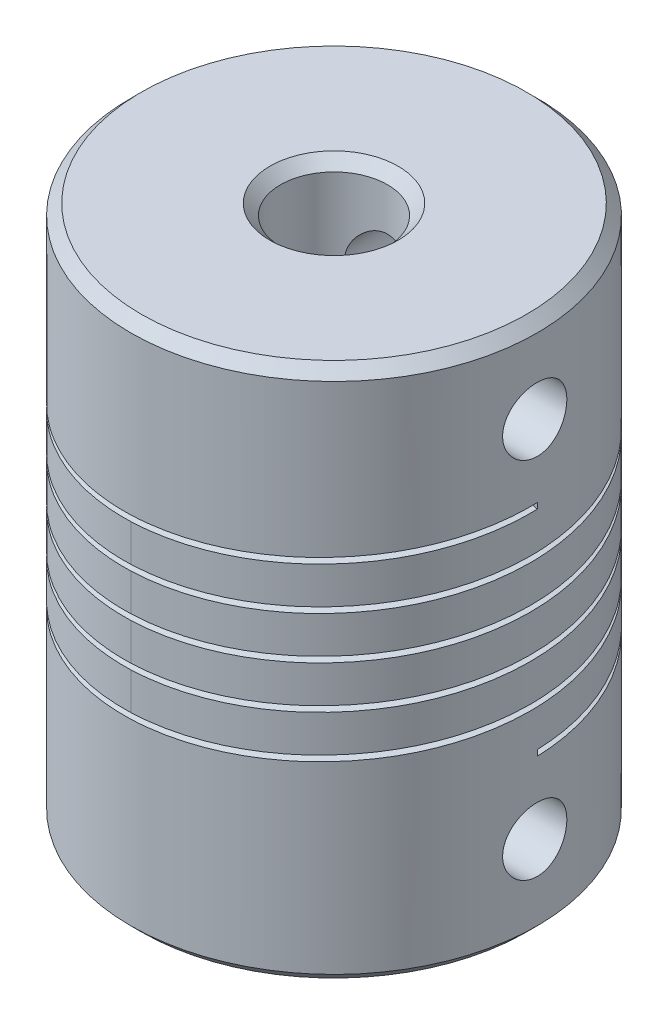
SolidWorks part; units mm, degrees
ref_plane "Front Plane" through (0, 0, 0) normal (0, 0, 1) x (1, 0, 0)
ref_plane "Top Plane" through (0, 0, 0) normal (0, 1, 0) x (1, 0, 0)
ref_plane "Right Plane" through (0, 0, 0) normal (1, 0, 0) x (0, 0, -1)
sketch "Sketch1" plane through (0, 0, 0) normal (0, 1, 0) x (1, 0, 0)
  circle A0 centre (0, 0) radius 9.5
  dimension "D1" = 19
extrude "Boss-Extrude1" add sketch "Sketch1" along normal mid plane 25
sketch "Sketch2" plane through (0, 12.5, 0) normal (0, 1, 0) x (1, 0, 0)
  circle A0 centre (0, 0) radius 2.5
  dimension "D1" = 5
extrude "Cut-Extrude1" cut sketch "Sketch2" against normal blind 12.5
sketch "Sketch3" plane through (0, -12.5, 0) normal (0, -1, 0) x (1, 0, 0)
  circle A0 centre (0, 0) radius 4
  dimension "D1" = 8
extrude "Cut-Extrude2" cut sketch "Sketch3" against normal blind 12.5
chamfer "Chamfer1" distance 0.5 angle 45 4 edges at (0, 12.5, 2.5) (0, 12.5, 9.5) (0, -12.5, 9.5) (0, -12.5, -4)
ref_plane "Plane1" through (0, -5, 0) normal (0, -1, 0) x (-1, 0, 0)
ref_plane "Plane2" through (0, 5, 0) normal (0, 1, 0) x (1, 0, 0)
sketch "Sketch4" plane through (0, -5, 0) normal (0, -1, 0) x (-1, 0, 0)
  circle A0 centre (0, 0) radius 9.5
  circle A1 centre (0, 0) radius 9.5 construction
curve "Helix/Spiral1" pitch 2 height 10 turns 5
sketch "Sketch5" plane through (0, 0, 0) normal (0, 0, 1) x (1, 0, 0)
  line L0 (10, 5.2679) -> (9, 5)
  line L1 (9.9, 5) -> (-9.9, 5) construction
  line L2 (9, 5) -> (10, 4.7321)
  line L3 (10, 4.7321) -> (10, 5.2679)
  line L4 (9, 5) -> (10, 5) construction
  line L5 (9.5, -12) -> (9.5, 12) construction
  point P4 (10, 5)
  point P6 (9.5, 5)
  dimension "D1" = 1
  dimension "D2" = 30
sweep "Cut-Sweep1" cut profiles "Sketch5" path "Helix/Spiral1"
sketch "Sketch6" plane through (0, 0, 0) normal (0, 0, 1) x (1, 0, 0)
  line L0 (0, -55) -> (0, 55) construction
  line L1 (9, 12.5) -> (-9, 12.5) construction
  circle A0 centre (0, 8.5) radius 1.5
  dimension "D1" = 3
  dimension "D2" = 4
extrude "Cut-Extrude3" cut sketch "Sketch6" against normal up to next
pattern_circular "CirPattern1" count 2 every 90 about axis through (0, 12.5, 0) along (0, -1, 0) of "Cut-Extrude3"
mirror "Mirror1" about plane through (0, 0, 0) normal (0, 1, 0) of "CirPattern1", "Cut-Extrude3"
equation "\"d1\"= 5"
equation "\"d2\"= 8"
equation "\"d_outer\"= 19"
equation "\"l\"= 25"
equation "\"D1@Sketch1\"=\"d_outer\""
equation "\"D1@Boss-Extrude1\"=\"l\""
equation "\"D1@Sketch2\"=\"d1\""
equation "\"D1@Cut-Extrude1\"=\"l\" / 2"
equation "\"D1@Sketch3\"=\"d2\""
equation "\"D1@Cut-Extrude2\"=\"l\" / 2"
